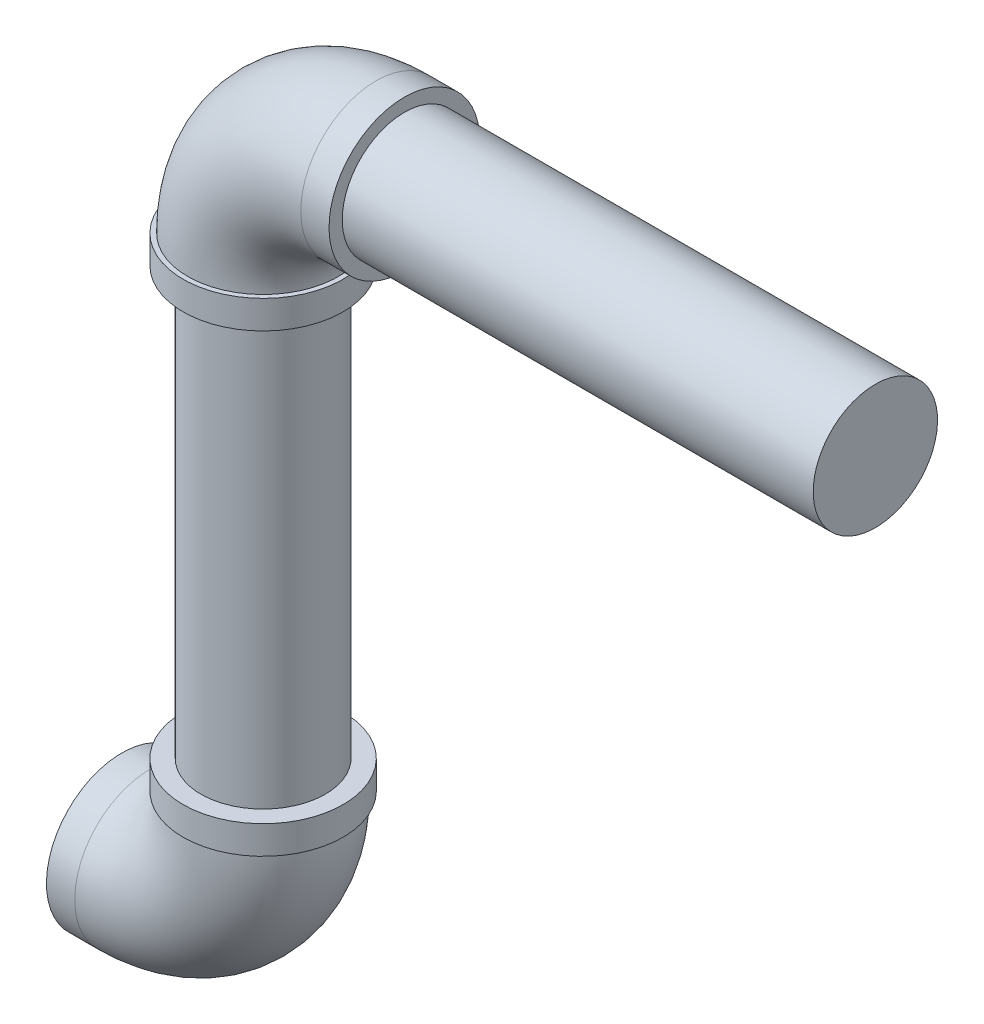
SolidWorks part; units mm, degrees
ref_plane "Front Plane" through (0, 0, 0) normal (0, 0, 1) x (1, 0, 0)
ref_plane "Top Plane" through (0, 0, 0) normal (0, 1, 0) x (1, 0, 0)
ref_plane "Right Plane" through (0, 0, 0) normal (1, 0, 0) x (0, 0, -1)
sketch "Sketch1" plane through (0, 0, 0) normal (0, 1, 0) x (1, 0, 0)
  circle A0 centre (0, 0) radius 16.764
  dimension "D1" = 33.528
extrude "Boss-Extrude1" add sketch "Sketch1" along normal mid plane 115.062 contours A0
sketch "Sketch3" plane through (0, 57.531, 0) normal (0, 1, 0) x (1, 0, 0)
  circle A0 centre (0, 0) radius 21.59
  dimension "D1" = 43.18
extrude "Boss-Extrude2" add sketch "Sketch3" along normal blind 7.62
sketch "Sketch4" plane through (0, 0, 0) normal (0, 0, 1) x (1, 0, 0)
  line L0 (21.59, 65.151) -> (-21.59, 65.151) construction
  arc A0 (0, 65.151) -> (30.48, 95.631) centre (30.48, 65.151) cw
  dimension "D1" = 30.48
  dimension "D2" = 30.48
sketch "Sketch5" plane through (0, 65.151, 0) normal (0, 1, 0) x (1, 0, 0)
  circle A0 centre (0, 0) radius 20.32
  dimension "D1" = 40.64
sweep "Sweep1" add profiles "Sketch5" path "Sketch4"
sketch "Sketch6" plane through (30.48, 0, 0) normal (1, 0, 0) x (0, 0, -1)
  circle A0 centre (0, 95.631) radius 21.59
  circle A2 centre (0, 95.631) radius 20.32
  circle A3 centre (0, 95.631) radius 20.32
  point P2 (58.492, 88.0658)
  point P3 (0, 0)
  dimension "D1" = 43.18
  dimension "D2" = 0
extrude "Boss-Extrude3" add sketch "Sketch6" along normal blind 7.62 contours A3
sketch "Sketch8" plane through (0, 0, 0) normal (1, 0, 0) x (0, 0, -1)
  line L0 (0, 0) -> (-115.8865, 0)
pattern_circular "CirPattern1" count 2 over 360 about axis through (0, 0, 0) along (0, 0, 1) of "Boss-Extrude2", "Sweep1", "Boss-Extrude3"
sketch "Sketch9" plane through (38.1, 0, 0) normal (1, 0, 0) x (0, 0, -1)
  circle A0 centre (0, 95.631) radius 16.764
  dimension "D1" = 33.528
extrude "Boss-Extrude4" add sketch "Sketch9" along normal blind 127
